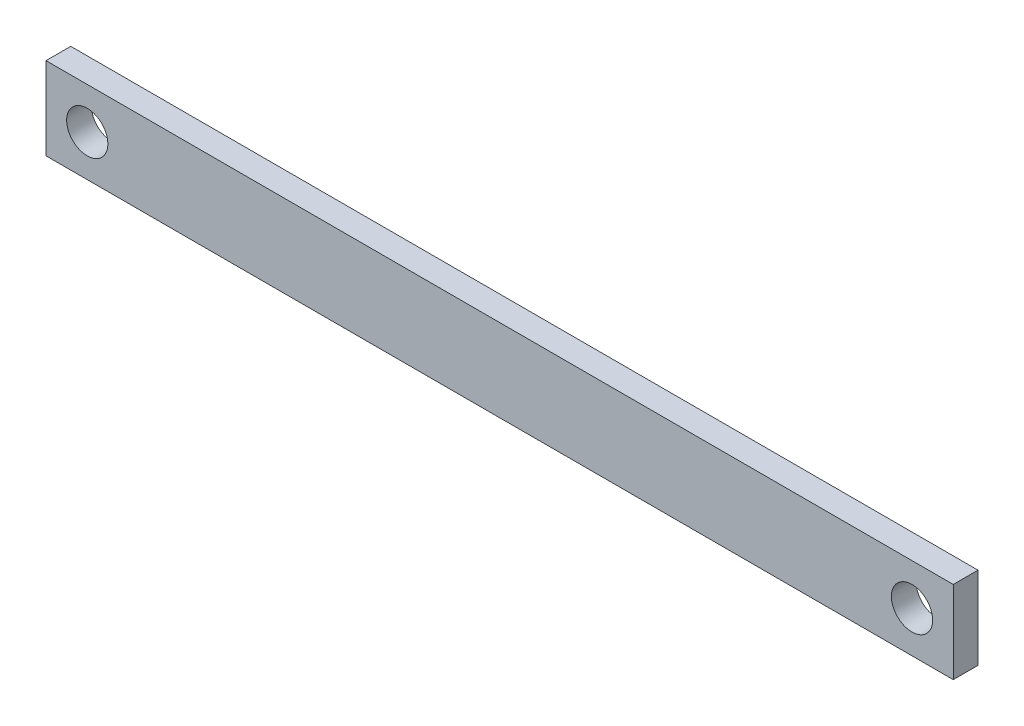
SolidWorks part; units mm, degrees
ref_plane "前基準面" through (0, 0, 0) normal (0, 0, 1) x (1, 0, 0)
ref_plane "上基準面" through (0, 0, 0) normal (0, 1, 0) x (1, 0, 0)
ref_plane "右基準面" through (0, 0, 0) normal (1, 0, 0) x (0, 0, -1)
sketch "草圖1" plane through (0, 0, 0) normal (0, 0, 1) x (1, 0, 0)
  line L0 (-55, 0) -> (55, 0) construction
  line L1 (-55, -5) -> (55, -5)
  line L2 (-55, -5) -> (-55, 5)
  line L3 (-55, 5) -> (55, 5)
  line L4 (55, -5) -> (55, 5)
  line L5 (-55, -5) -> (55, 5) construction
  line L6 (-55, 5) -> (55, -5) construction
  circle A0 centre (-50, 0) radius 2.5
  circle A1 centre (50, 0) radius 2.5
  point P0 (0, 0)
  dimension "D5" = 5
  dimension "D6" = 5
  dimension "D1" = 110
  dimension "D2" = 10
  dimension "D3" = 50
  dimension "D4" = 50
extrude "填料-伸長1" add sketch "草圖1" along normal blind 3
